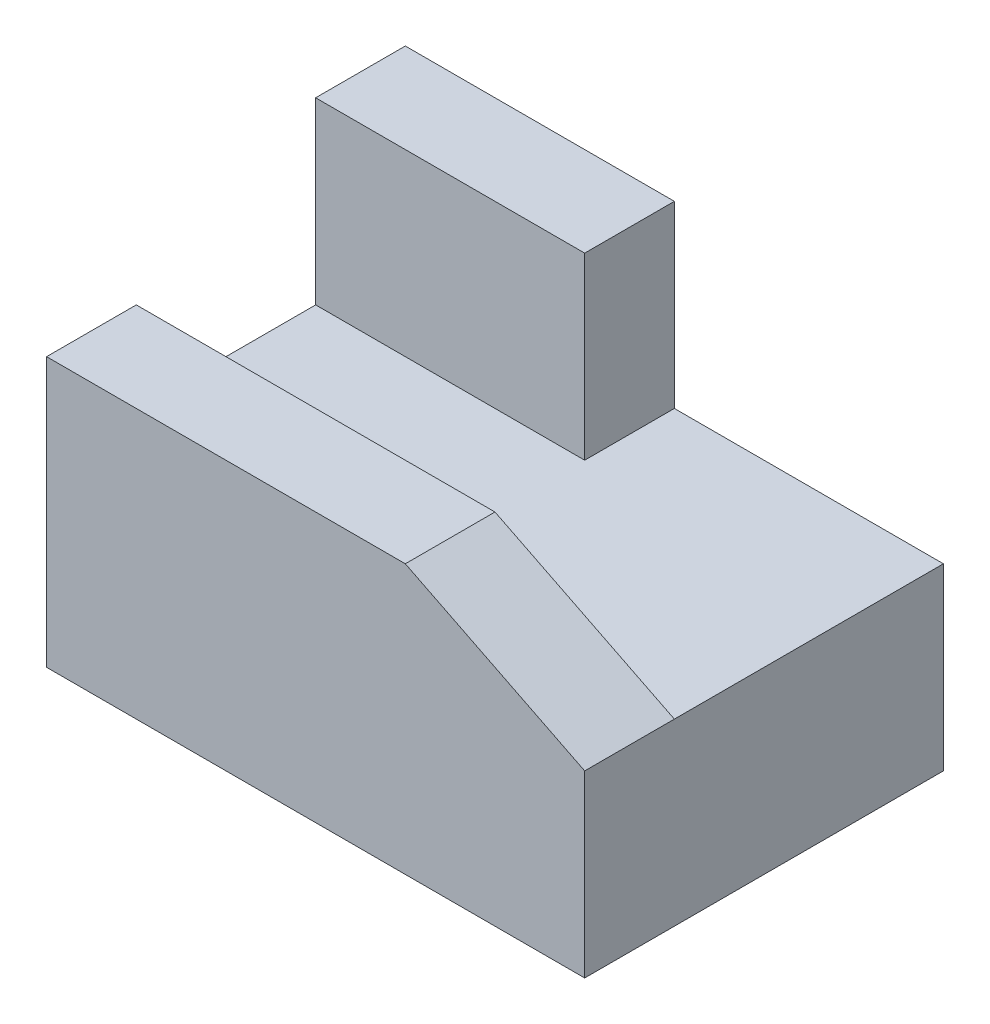
SolidWorks part; units mm, degrees
ref_plane "前基準面" through (0, 0, 0) normal (0, 0, 1) x (1, 0, 0)
ref_plane "上基準面" through (0, 0, 0) normal (0, 1, 0) x (1, 0, 0)
ref_plane "右基準面" through (0, 0, 0) normal (1, 0, 0) x (0, 0, -1)
sketch "草圖1" plane through (0, 0, 0) normal (0, 1, 0) x (1, 0, 0)
  line L1 (0, 0) -> (30, 0)
  line L2 (0, 0) -> (0, 20)
  line L3 (0, 20) -> (30, 20)
  line L4 (30, 0) -> (30, 20)
  dimension "D1" = 30
  dimension "D2" = 20
extrude "填料-伸長1" add sketch "草圖1" along normal blind 10
sketch "草圖2" plane through (0, 0, 0) normal (0, 0, 1) x (1, 0, 0)
  line L0 (0, 10) -> (0, 15)
  line L1 (0, 15) -> (20, 15)
  line L2 (20, 15) -> (30, 10)
  line L3 (30, 10) -> (0, 10)
  dimension "D1" = 5
  dimension "D2" = 20
extrude "填料-伸長2" add sketch "草圖2" against normal blind 5
sketch "草圖4" plane through (0, 0, -20) normal (0, 0, -1) x (-1, 0, 0)
  line L1 (0, 10) -> (-15, 10)
  line L2 (0, 10) -> (0, 20)
  line L3 (0, 20) -> (-15, 20)
  line L4 (-15, 10) -> (-15, 20)
  dimension "D1" = 10
  dimension "D2" = 15
extrude "填料-伸長3" add sketch "草圖4" against normal blind 5
